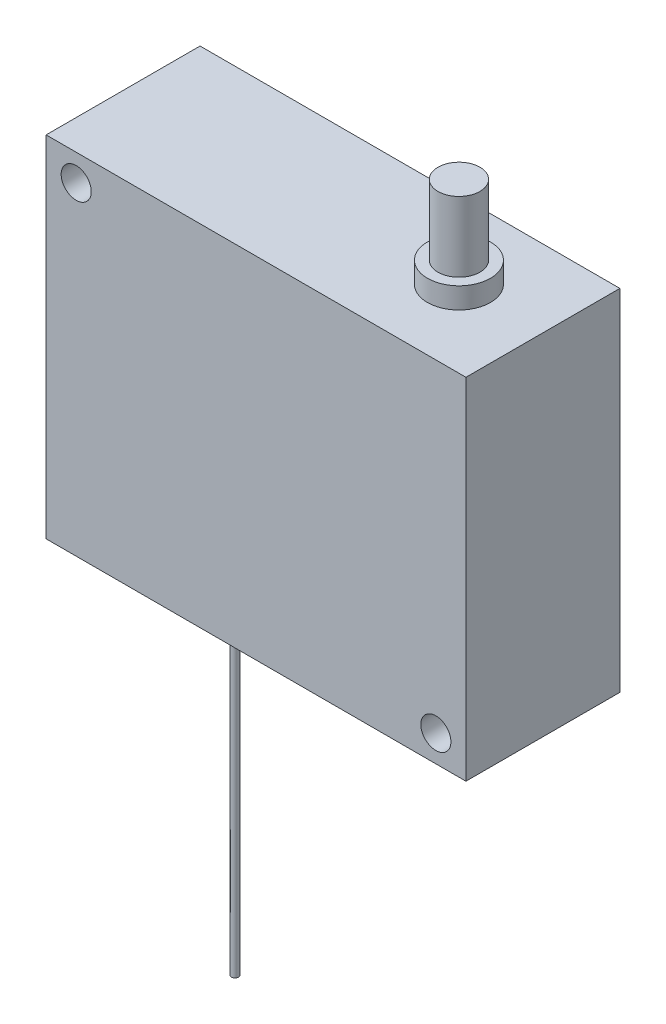
SolidWorks part; units mm, degrees
ref_plane "前视基准面" through (0, 0, 0) normal (0, 0, 1) x (1, 0, 0)
ref_plane "上视基准面" through (0, 0, 0) normal (0, 1, 0) x (1, 0, 0)
ref_plane "右视基准面" through (0, 0, 0) normal (1, 0, 0) x (0, 0, -1)
sketch "草图1" plane through (0, 0, 0) normal (0, 0, 1) x (1, 0, 0)
  line L1 (0, 0) -> (60, 0)
  line L2 (0, 0) -> (0, 50)
  line L3 (0, 50) -> (60, 50)
  line L4 (60, 0) -> (60, 50)
  dimension "D1" = 50
  dimension "D2" = 60
extrude "凸台-拉伸1" add sketch "草图1" along normal blind 22
sketch "草图2" plane through (0, 50, 0) normal (0, 1, 0) x (1, 0, 0)
  line L0 (60, -11) -> (28.0051, -11) construction
  line L1 (60, -22) -> (60, 0) construction
  circle A0 centre (48, -11) radius 4.5
  dimension "D1" = 9
  dimension "D2" = 12
extrude "凸台-拉伸2" add sketch "草图2" along normal blind 3
sketch "草图3" plane through (0, 53, 0) normal (0, 1, 0) x (1, 0, 0)
  circle A0 centre (48, -11) radius 3
  dimension "D1" = 6
extrude "凸台-拉伸3" add sketch "草图3" along normal blind 10
sketch "草图5" plane through (0, 0, 0) normal (0, -1, 0) x (1, 0, 0)
  line L0 (3, 7.5) -> (25.1759, 7.5) construction
  line L1 (3, 11.5) -> (42, 11.5)
  line L2 (3, 11.5) -> (3, 3.5)
  line L3 (3, 3.5) -> (42, 3.5)
  line L4 (42, 11.5) -> (42, 3.5)
  line L5 (0, 0) -> (60, 0) construction
  line L6 (0, 22) -> (0, 0) construction
  line L7 (60, 22) -> (60, 0) construction
  dimension "D1" = 7.5
  dimension "D2" = 8
  dimension "D3" = 3
  dimension "D4" = 18
sketch "草图4" plane through (0, 0, 0) normal (0, -1, 0) x (1, 0, 0)
  line L0 (0, 0) -> (60, 0) construction
  line L1 (0, 22) -> (0, 0) construction
  circle A0 centre (12.5, 7.5) radius 0.5
  dimension "D1" = 1
  dimension "D3" = 12.5
  dimension "D2" = 7.5
extrude "凸台-拉伸4" add sketch "草图4" along normal blind 55
extrude "切除-拉伸1" cut sketch "草图5" against normal blind 0.01
sketch "草图6" plane through (0, 0, 22) normal (0, 0, 1) x (1, 0, 0)
  line L0 (0, 50) -> (0, 0) construction
  line L1 (0, 0) -> (60, 0) construction
  circle A0 centre (55.7, 3.8) radius 2.15
  circle A1 centre (4.3, 46.2) radius 2.15
  dimension "D1" = 4.3
  dimension "D2" = 42.4
  dimension "D3" = 51.4
  dimension "D4" = 4.3
  dimension "D5" = 3.8
extrude "切除-拉伸2" cut sketch "草图6" against normal through all
